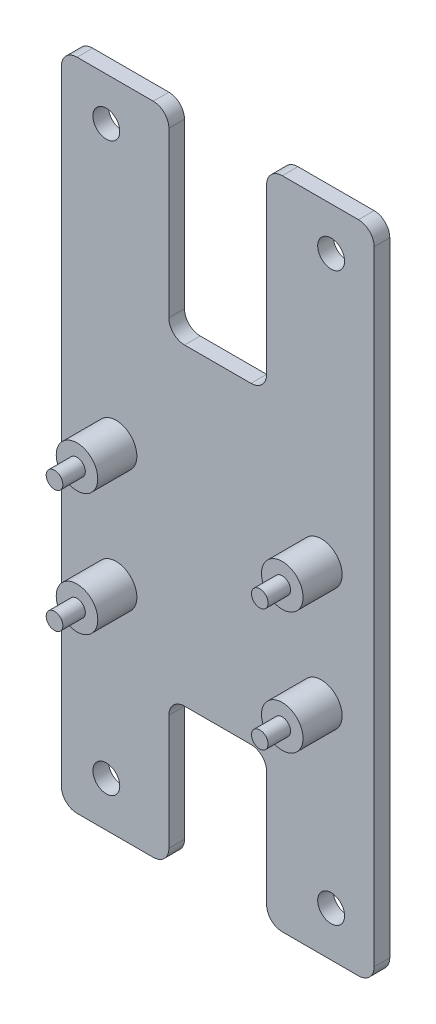
SolidWorks part; units mm, degrees
ref_plane "Płaszczyzna przednia" through (0, 0, 0) normal (0, 0, 1) x (1, 0, 0)
ref_plane "Płaszczyzna górna" through (0, 0, 0) normal (0, 1, 0) x (1, 0, 0)
ref_plane "Płaszczyzna prawa" through (0, 0, 0) normal (1, 0, 0) x (0, 0, -1)
other "Grafika1"
other "Grafika (Zamknięta) -1"
sketch "Szkic2" plane through (0, 0, 0) normal (0, 0, 1) x (1, 0, 0)
  line L0 (0, 0) -> (32, 0)
  line L1 (0, 0) -> (0, 67)
  line L2 (0, 67) -> (32, 67)
  line L3 (32, 67) -> (32, 0)
  circle A0 centre (4.6, 4.6) radius 1.375
  circle A1 centre (27.6, 4.6) radius 1.375
  circle A2 centre (27.6, 62.6) radius 1.375
  circle A3 centre (4.6, 62.6) radius 1.375
  dimension "D1" = 32
  dimension "D2" = 67
extrude "Dodanie-wyciągnięcie1" add sketch "Szkic2" along normal blind 1.6
sketch "Szkic3" plane through (0, 0, 1.6) normal (0, 0, 1) x (1, 0, 0)
  circle A0 centre (5.6, 34.7) radius 2.125
  circle A1 centre (26.6, 34.7) radius 2.125
  circle A2 centre (5.6, 22.2) radius 2.125
  circle A3 centre (26.6, 22.2) radius 2.125
extrude "Dodanie-wyciągnięcie2" add sketch "Szkic3" along normal blind 4
sketch "Szkic4" plane through (0, 0, 5.6) normal (0, 0, 1) x (1, 0, 0)
  circle A0 centre (5.6, 34.7) radius 0.85
  circle A1 centre (26.6, 34.7) radius 0.85
  circle A2 centre (5.6, 22.2) radius 0.85
  circle A3 centre (26.6, 22.2) radius 0.85
  point P0 (5.6, 34.7)
  point P1 (26.6, 34.7)
  point P3 (26.6, 22.2)
  point P5 (5.6, 22.2)
  dimension "D1" = 1.7
  dimension "D2" = 1.7
  dimension "D3" = 1.7
  dimension "D4" = 1.7
extrude "Dodanie-wyciągnięcie3" add sketch "Szkic4" along normal blind 2.3
sketch "Szkic5" plane through (0, 0, 1.6) normal (0, 0, 1) x (1, 0, 0)
  line L0 (11, 47) -> (11, 67)
  line L3 (16, 47) -> (16, 67) construction
  line L4 (11, 0) -> (11, 15)
  line L5 (0, 0) -> (32, 0) construction
  line L6 (32, 67) -> (0, 67) construction
  line L7 (21, 67) -> (21, 47)
  line L8 (16, 0) -> (16, 15) construction
  line L9 (11, 67) -> (21, 67)
  line L10 (11, 0) -> (21, 0)
  line L11 (11, 15) -> (21, 15)
  line L12 (11, 47) -> (21, 47)
  line L13 (21, 15) -> (21, 0)
  point P0 (0, 0)
  dimension "D1" = 5
  dimension "D2" = 5
  dimension "D3" = 15
  dimension "D4" = 20
extrude "Wytnij-wyciągnięcie1" cut sketch "Szkic5" against normal through all both and the other way through all
fillet "Zaokrąglenie1" radius 1.6 12 edges at (21, 47, 0.8) (11, 47, 0.8) (11, 15, 0.8) (21, 15, 0.8) (21, 0, 0.8) (32, 0, 0.8) (32, 67, 0.8) (21, 67, 0.8) (0, 67, 0.8) (11, 67, 0.8) (0, 0, 0.8) (11, 0, 0.8)
